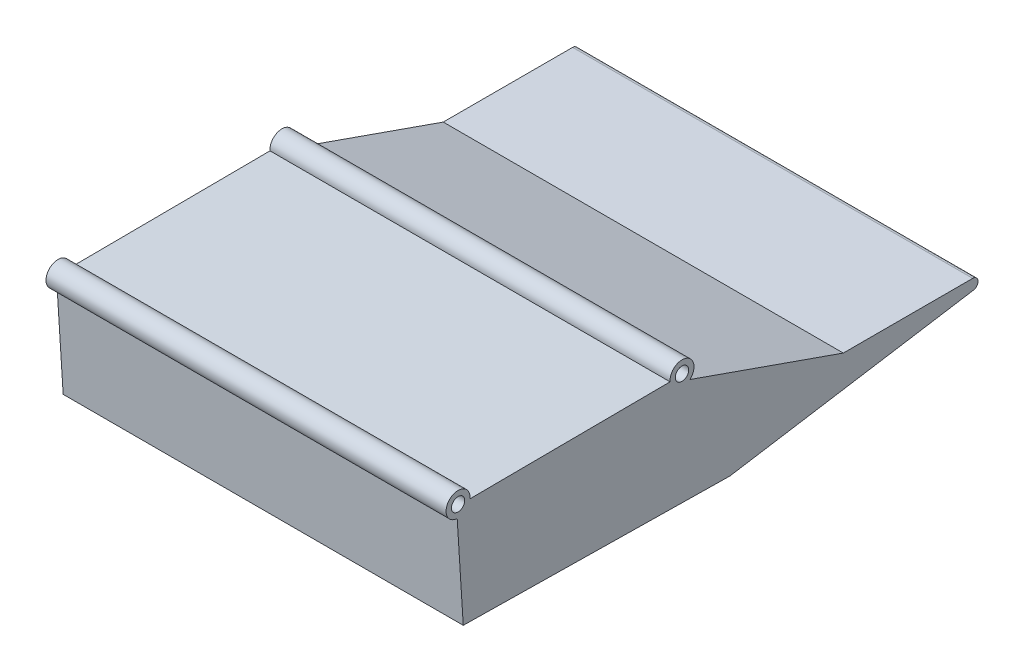
SolidWorks part; units mm, degrees
ref_plane "Plano frontal" through (0, 0, 0) normal (0, 0, 1) x (1, 0, 0)
ref_plane "Plano superior" through (0, 0, 0) normal (0, 1, 0) x (1, 0, 0)
ref_plane "Plano direito" through (0, 0, 0) normal (1, 0, 0) x (0, 0, -1)
sketch "Esboço1" plane through (0, 0, 0) normal (1, 0, 0) x (0, 0, -1)
  line L8 (-100, -17.8481) -> (0, -19.3473)
  line L9 (42.4967, -0.6831) -> (-15.0065, 19.4805)
  line L14 (-22.459, 22.4502) -> (-97.4607, 21.9754)
  line L15 (-102.268, 17.9419) -> (-100, -17.8481)
  line L16 (42.4967, -0.6831) -> (116.0205, -0.6831)
  line L17 (116.0205, -0.6831) -> (0, -19.3473)
  circle A4 centre (-101.9377, 22.4298) radius 2.5
  circle A5 centre (-17.9777, 22.8602) radius 2.5
  arc A6 (-97.4607, 21.9754) -> (-102.268, 17.9419) centre (-101.9377, 22.4298) ccw
  arc A7 (-15.0065, 19.4805) -> (-22.459, 22.4502) centre (-17.9777, 22.8602) ccw
  dimension "D6" = 35.79
  dimension "D8" = 2
  dimension "D9" = 2
  dimension "D5" = 5
  dimension "D2" = 5
  dimension "D3" = 83.96
extrude "Ressalto-extrusão1" add sketch "Esboço1" along normal mid plane 150
fillet "Filete1" radius 2 1 edges at (0, -0.6831, -116.0205)
